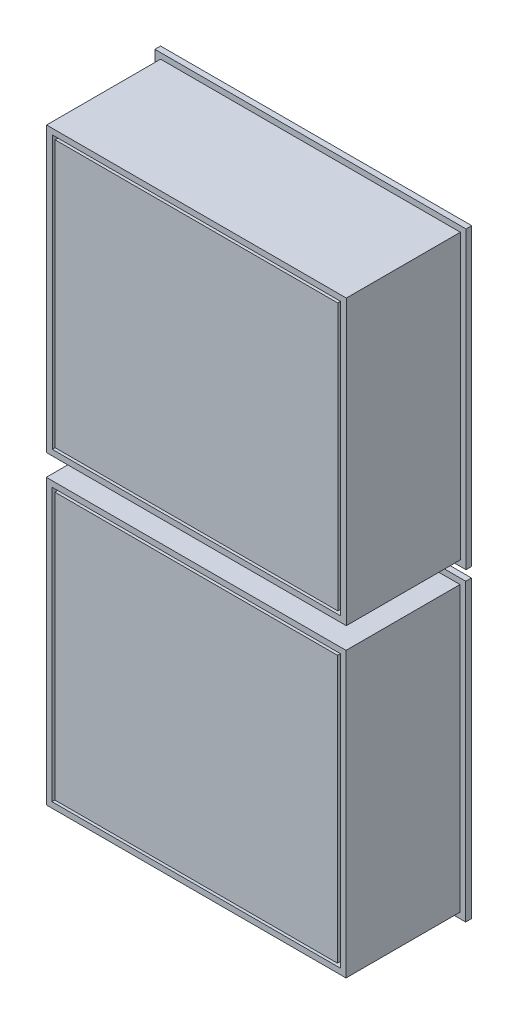
SolidWorks part; units mm, degrees
material "ABS"
ref_plane "Front Plane" through (0, 0, 0) normal (0, 0, 1) x (1, 0, 0)
ref_plane "Top Plane" through (0, 0, 0) normal (0, 1, 0) x (1, 0, 0)
ref_plane "Right Plane" through (0, 0, 0) normal (1, 0, 0) x (0, 0, -1)
sketch "Sketch1" plane through (0, 0, 0) normal (0, 0, 1) x (1, 0, 0)
  line L0 (26.1454, -13.9806) -> (-26.4388, -13.9806)
  line L5 (26.1454, -13.9806) -> (26.1454, -63.7589)
  line L6 (26.1454, -63.7589) -> (-26.4388, -63.7589)
  line L7 (-26.4388, -13.9806) -> (-26.4388, -63.7589)
  line L8 (26.1987, 39.5675) -> (-26.3854, 39.5675)
  line L9 (26.1987, 39.5675) -> (26.1987, -10.2108)
  line L10 (26.1987, -10.2108) -> (-26.3854, -10.2108)
  line L11 (-26.3854, 39.5675) -> (-26.3854, -10.2108)
  point P10 (27.5001, -63.08)
extrude "Boss-Extrude1" add sketch "Sketch1" along normal blind 20
sketch "Sketch4" plane through (0, 0, 0) normal (0, 0, -1) x (-1, 0, 0)
  line L8 (27.3854, -11.2108) -> (27.3854, 40.5675)
  line L9 (-27.1987, -11.2108) -> (27.3854, -11.2108)
  line L10 (-27.1987, 40.5675) -> (-27.1987, -11.2108)
  line L11 (27.3854, 40.5675) -> (-27.1987, 40.5675)
  line L12 (27.3854, -11.2108) -> (27.3854, 40.5675)
  line L13 (-27.1987, -11.2108) -> (27.3854, -11.2108)
  line L14 (-27.1987, 40.5675) -> (-27.1987, -11.2108)
  line L15 (27.3854, 40.5675) -> (-27.1987, 40.5675)
  line L20 (25.9388, -63.2589) -> (25.9388, -14.4806)
  line L21 (-25.6454, -63.2589) -> (25.9388, -63.2589)
  line L22 (-25.6454, -14.4806) -> (-25.6454, -63.2589)
  line L23 (25.9388, -14.4806) -> (-25.6454, -14.4806)
  line L24 (25.9388, -63.2589) -> (25.9388, -14.4806)
  line L25 (-25.6454, -63.2589) -> (25.9388, -63.2589)
  line L26 (-25.6454, -14.4806) -> (-25.6454, -63.2589)
  line L27 (25.9388, -14.4806) -> (-25.6454, -14.4806)
  dimension "D1" = 1
  dimension "D2" = 0.5
extrude "Boss-Extrude2" add sketch "Sketch4" along normal blind 1 contours L13 L12 L15 L14
sketch "Sketch5" plane through (0, 0, -1) normal (0, 0, -1) x (-1, 0, 0)
  line L4 (-24.6987, 38.0675) -> (-24.6987, -8.7108)
  line L5 (-24.6987, -8.7108) -> (24.8854, -8.7108)
  line L6 (24.8854, -8.7108) -> (24.8854, 38.0675)
  line L7 (24.8854, 38.0675) -> (-24.6987, 38.0675)
  line L8 (-25.1987, -9.2108) -> (25.3854, -9.2108)
  line L9 (25.3854, -9.2108) -> (25.3854, 38.5675)
  line L10 (-25.1987, 38.5675) -> (-25.1987, -9.2108)
  line L11 (25.3854, 38.5675) -> (-25.1987, 38.5675)
  line L12 (-25.1987, -9.2108) -> (25.3854, -9.2108)
  line L13 (25.3854, -9.2108) -> (25.3854, 38.5675)
  line L14 (-25.1987, 38.5675) -> (-25.1987, -9.2108)
  line L15 (25.3854, 38.5675) -> (-25.1987, 38.5675)
  dimension "D1" = 2
  dimension "D2" = 0.5
extrude "Cut-Extrude3" cut sketch "Sketch5" against normal through all
sketch "Sketch6" plane through (0, 0, 0) normal (0, 0, -1) x (-1, 0, 0)
  line L8 (-27.1454, -64.7589) -> (27.4388, -64.7589)
  line L9 (27.4388, -64.7589) -> (27.4388, -12.9806)
  line L10 (-27.1454, -12.9806) -> (-27.1454, -64.7589)
  line L11 (27.4388, -12.9806) -> (-27.1454, -12.9806)
  line L12 (-27.1454, -64.7589) -> (27.4388, -64.7589)
  line L13 (27.4388, -64.7589) -> (27.4388, -12.9806)
  line L14 (-27.1454, -12.9806) -> (-27.1454, -64.7589)
  line L15 (27.4388, -12.9806) -> (-27.1454, -12.9806)
  dimension "D1" = 1
extrude "Boss-Extrude3" add sketch "Sketch6" along normal through all
sketch "Sketch7" plane through (0, 0, -1) normal (0, 0, -1) x (-1, 0, 0)
  line L4 (24.9388, -62.2589) -> (24.9388, -15.4806)
  line L5 (24.9388, -15.4806) -> (-24.6454, -15.4806)
  line L6 (-24.6454, -15.4806) -> (-24.6454, -62.2589)
  line L7 (-24.6454, -62.2589) -> (24.9388, -62.2589)
  line L8 (25.4388, -62.7589) -> (25.4388, -14.9806)
  line L9 (-25.1454, -62.7589) -> (25.4388, -62.7589)
  line L10 (-25.1454, -14.9806) -> (-25.1454, -62.7589)
  line L11 (25.4388, -14.9806) -> (-25.1454, -14.9806)
  line L12 (25.4388, -62.7589) -> (25.4388, -14.9806)
  line L13 (-25.1454, -62.7589) -> (25.4388, -62.7589)
  line L14 (-25.1454, -14.9806) -> (-25.1454, -62.7589)
  line L15 (25.4388, -14.9806) -> (-25.1454, -14.9806)
  point P0 (25.4388, -14.9806)
  dimension "D1" = 2
  dimension "D2" = 0.5
extrude "Cut-Extrude4" cut sketch "Sketch7" against normal through all
